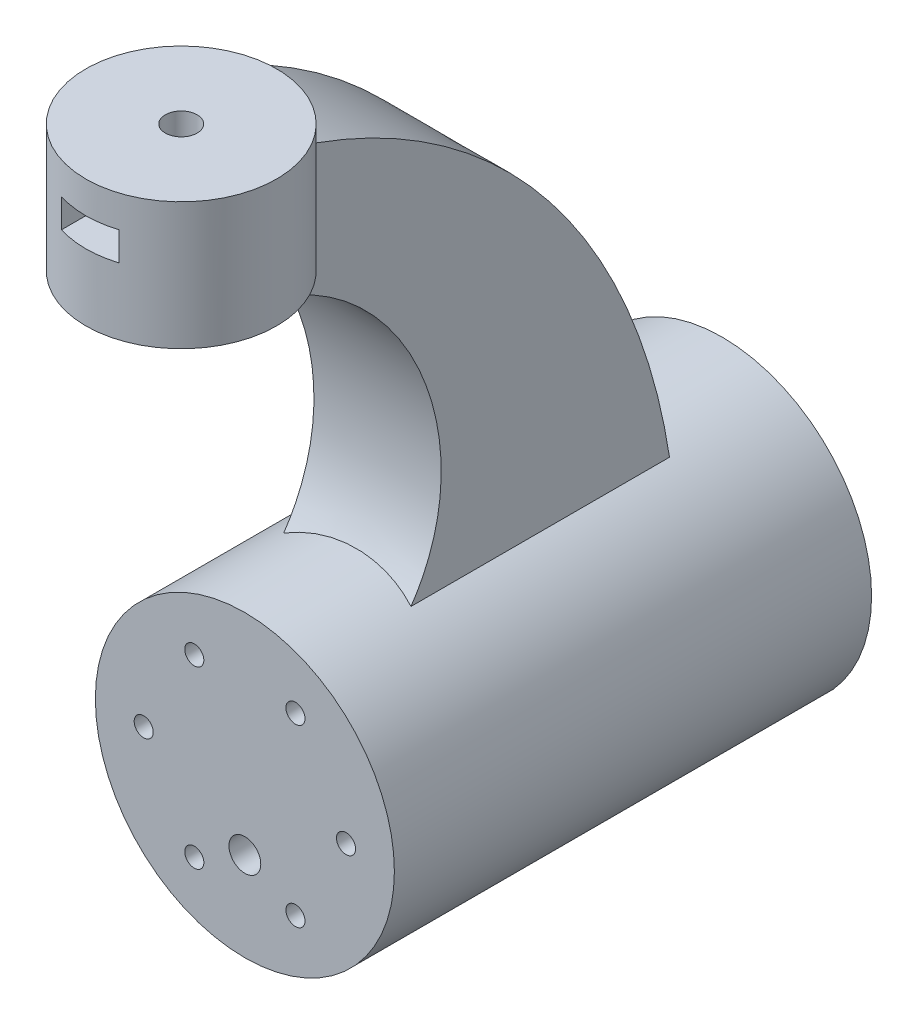
SolidWorks part; units mm, degrees
ref_plane "Front Plane" through (0, 0, 0) normal (0, 0, 1) x (1, 0, 0)
ref_plane "Top Plane" through (0, 0, 0) normal (0, 1, 0) x (1, 0, 0)
ref_plane "Right Plane" through (0, 0, 0) normal (1, 0, 0) x (0, 0, -1)
sketch "Sketch3" plane through (0, 0, 0) normal (0, 1, 0) x (1, 0, 0)
  circle A0 centre (0, 0) radius 15
  dimension "D1" = 30
extrude "Boss-Extrude1" add sketch "Sketch3" against normal blind 20
sketch "Sketch4" plane through (0, 0, 0) normal (0, 1, 0) x (1, 0, 0)
  circle A0 centre (0, 0) radius 2.5
  dimension "D1" = 5
extrude "Cut-Extrude1" cut sketch "Sketch4" against normal through all
ref_plane "Plane1" through (0, -5, 0) normal (0, 1, 0) x (1, 0, 0)
sketch "Sketch6" plane through (0, -5, 0) normal (0, 1, 0) x (1, 0, 0)
  line L1 (4.5, -2.5981) -> (4.5, 2.5981)
  line L2 (4.5, 2.5981) -> (0, 5.1962)
  line L3 (0, 5.1962) -> (-4.5, 2.5981)
  line L4 (-4.5, 2.5981) -> (-4.5, -2.5981)
  line L5 (-4.5, -2.5981) -> (0, -5.1962)
  line L6 (0, -5.1962) -> (4.5, -2.5981)
  circle A0 centre (0, 0) radius 4.5 construction
  dimension "D1" = 9
extrude "Cut-Extrude2" cut sketch "Sketch6" against normal blind 4.5
sketch "Sketch7" plane through (0, 0, 0) normal (0, 0, 1) x (1, 0, 0)
  line L0 (0, -9.5) -> (0, -5) construction
  line L1 (-4.5, -5) -> (4.5, -5)
  line L2 (-4.5, -5) -> (-4.5, -9.5)
  line L3 (-4.5, -9.5) -> (4.5, -9.5)
  line L4 (4.5, -5) -> (4.5, -9.5)
  line L5 (-4.5, -5) -> (4.5, -9.5) construction
  line L6 (-4.5, -9.5) -> (4.5, -5) construction
  point P0 (0, -7.25)
extrude "Cut-Extrude3" cut sketch "Sketch7" along normal through all
sketch "Sketch8" plane through (0, 0, 0) normal (1, 0, 0) x (0, 0, -1)
  line L0 (0, -10) -> (0, -80) construction
  line L1 (0, -50) -> (30, -50) construction
  line L2 (0, -65) -> (30, -65) construction
  line L3 (0, -80) -> (20, -80) construction
  line L4 (0, 0) -> (9.7998, 0) construction
  line L5 (0, -20) -> (-5.8962, -20) construction
  line L6 (-15, -20) -> (15, -20) construction
  line L7 (30, -50) -> (60, -50) construction
  line L8 (30, -65) -> (65, -65) construction
  line L9 (20, -80) -> (67.5, -80) construction
  line L10 (0, -20) -> (3.9895, -20)
  line L11 (0, 0) -> (0, -20)
  line L13 (20, -80) -> (67.5, -80)
  spline S0 degree 3 poles (0, -20) (27.2843, -24.0703) (42.4562, -63.4) (20, -80) knots 0 0 0 0 1 1 1 1
  spline S1 degree 3 poles (0, 0) (41.4153, -8.8948) (64.2406, -43.7742) (67.5, -80) knots 0 0 0 0 1 1 1 1
  dimension "D1" = 80
  dimension "D2" = 50
  dimension "D3" = 15
  dimension "D4" = 15
  dimension "D5" = 30
  dimension "D6" = 30
  dimension "D7" = 20
  dimension "D8" = 30
  dimension "D9" = 35
  dimension "D10" = 47.5
extrude "Boss-Extrude3" add sketch "Sketch8" along normal mid plane 20
sketch "Sketch9" plane through (0, 0, 0) normal (0, 1, 0) x (1, 0, 0)
  circle A0 centre (0, 0) radius 2.5
extrude "Cut-Extrude4" cut sketch "Sketch9" against normal blind 30
ref_plane "Plane2" through (0, 0, -10) normal (0, 0, 1) x (1, 0, 0)
sketch "Sketch12" plane through (0, 0, -10) normal (0, 0, 1) x (1, 0, 0)
  circle A0 centre (0, -95) radius 23.5
  dimension "D1" = 47
  dimension "D2" = 95
extrude "Boss-Extrude6" add sketch "Sketch12" against normal blind 75 contours A0
sketch "Sketch13" plane through (0, 0, -10) normal (0, 0, 1) x (1, 0, 0)
  circle A0 centre (0, -95) radius 19
  circle A1 centre (0, -95) radius 23.5 construction
  dimension "D1" = 38
extrude "Cut-Extrude6" cut sketch "Sketch13" against normal through all
sketch "Sketch14" plane through (0, 0, -10) normal (0, 0, 1) x (1, 0, 0)
  circle A0 centre (0, -95) radius 19
  circle A1 centre (0, -95) radius 19 construction
extrude "Boss-Extrude7" add sketch "Sketch14" against normal blind 5
sketch "Sketch15" plane through (0, 0, -10) normal (0, 0, 1) x (1, 0, 0)
  line L0 (15.9, -95) -> (0, -95) construction
  circle A0 centre (15.9, -95) radius 1.5
  circle A1 centre (7.95, -108.7698) radius 1.5
  circle A2 centre (-7.95, -108.7698) radius 1.5
  circle A3 centre (-15.9, -95) radius 1.5
  circle A4 centre (-7.95, -81.2302) radius 1.5
  circle A5 centre (7.95, -81.2302) radius 1.5
  circle A7 centre (0, -104.5) radius 2.5
  dimension "D1" = 3
  dimension "D4" = 5
  dimension "D2" = 15.9
  dimension "D5" = 9.5
  dimension "D3" = 6
extrude "Cut-Extrude8" cut sketch "Sketch15" against normal blind 5
